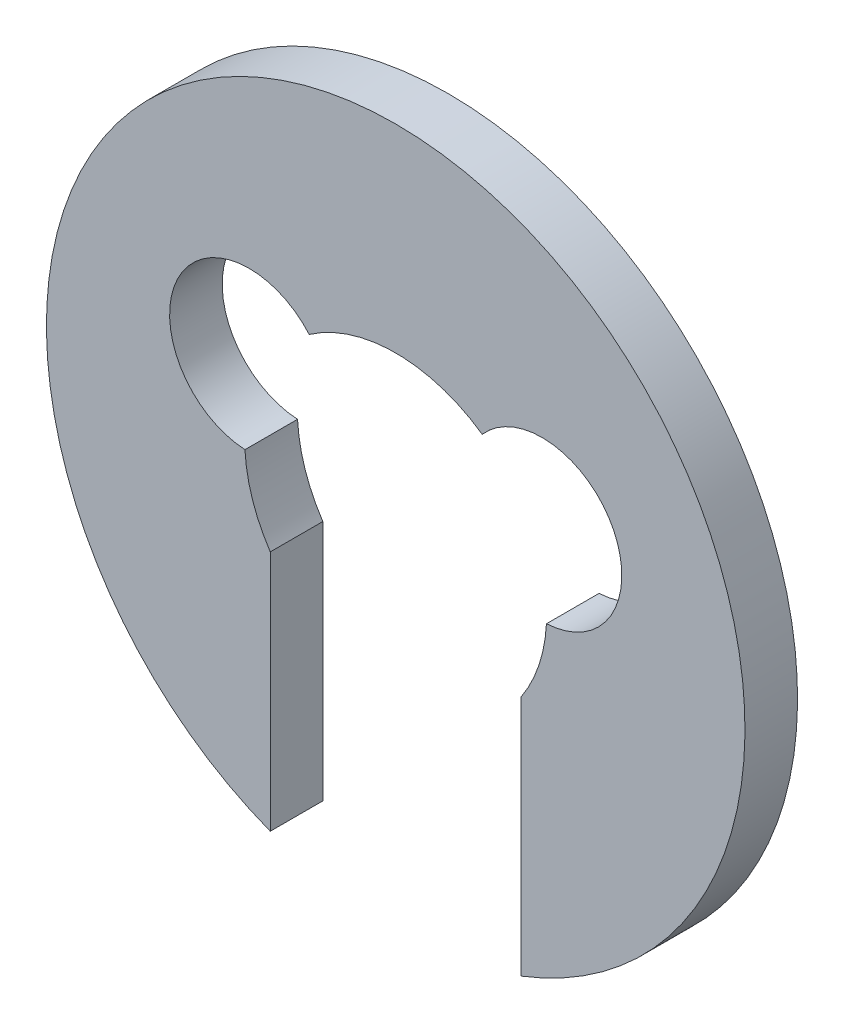
SolidWorks part; units mm, degrees
ref_plane "Front Plane" through (0, 0, 0) normal (0, 0, 1) x (1, 0, 0)
ref_plane "Top Plane" through (0, 0, 0) normal (0, 1, 0) x (1, 0, 0)
ref_plane "Right Plane" through (0, 0, 0) normal (1, 0, 0) x (0, 0, -1)
sketch "S01 - Installed spring clip envelope" plane through (0, 0, 0) normal (0, 0, 1) x (1, 0, 0)
  circle A0 centre (0, 0) radius 4.65
  circle A1 centre (0, 0) radius 2.01
extrude "01 - Installed spring clip envelope" add sketch "S01 - Installed spring clip envelope" along normal blind 0.7 from offset 7.48
sketch "S02 - Radial entry opening" plane through (0, 0, 0) normal (0, 0, 1) x (1, 0, 0)
  line L0 (-1.67, -4.8) -> (1.67, -4.8)
  line L1 (1.67, -4.8) -> (1.67, 0.3)
  line L2 (1.67, 0.3) -> (-1.67, 0.3)
  line L3 (-1.67, 0.3) -> (-1.67, -4.8)
extrude "02 - Radial entry opening" cut sketch "S02 - Radial entry opening" along normal blind 0.75 from offset 7.46
sketch "S03 - Left spring relief" plane through (0, 0, 0) normal (0, 0, 1) x (1, 0, 0)
  circle A0 centre (-1.95, 0.95) radius 1.06
extrude "03 - Left spring relief" cut sketch "S03 - Left spring relief" along normal blind 0.75 from offset 7.46
sketch "S04 - Right spring relief" plane through (0, 0, 0) normal (0, 0, 1) x (1, 0, 0)
  circle A0 centre (1.95, 0.95) radius 1.06
extrude "04 - Right spring relief" cut sketch "S04 - Right spring relief" along normal blind 0.75 from offset 7.46
